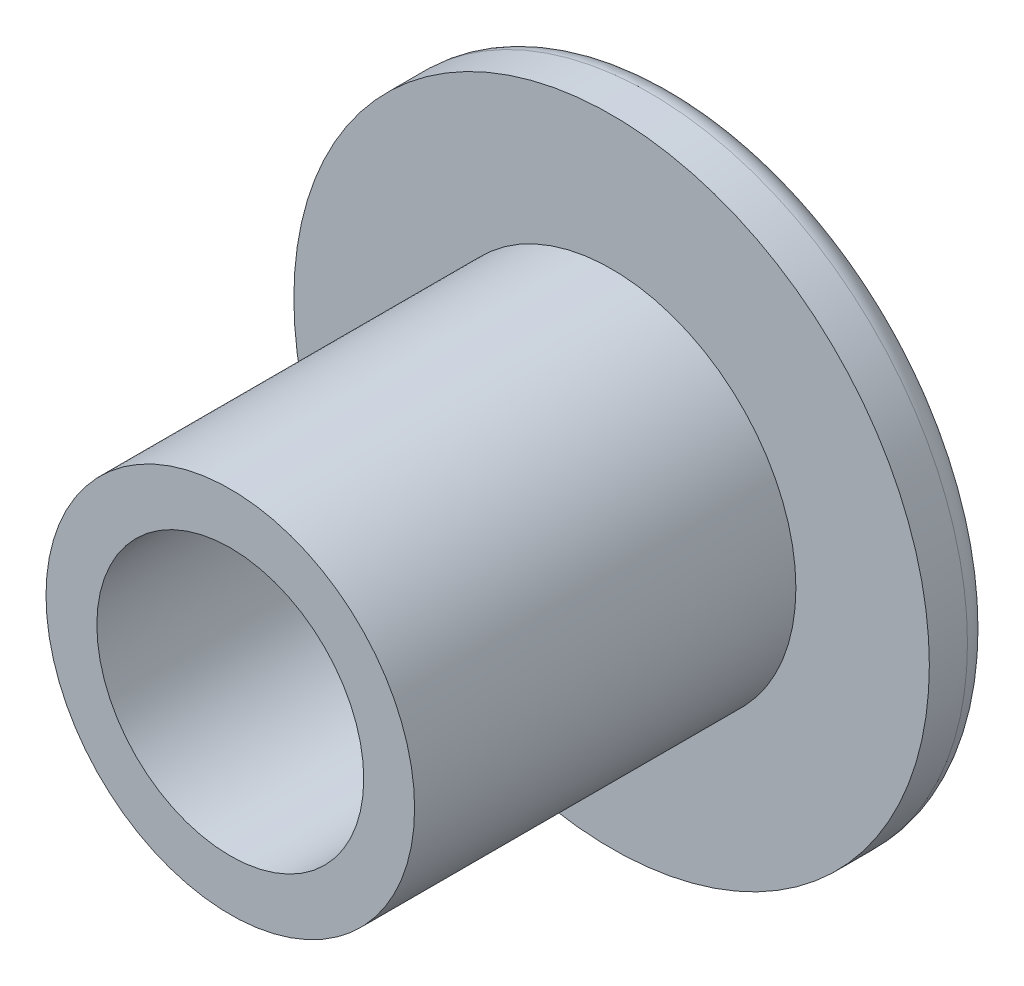
SolidWorks part; units mm, degrees
ref_plane "Front Plane" through (0, 0, 0) normal (0, 0, 1) x (1, 0, 0)
ref_plane "Top Plane" through (0, 0, 0) normal (0, 1, 0) x (1, 0, 0)
ref_plane "Right Plane" through (0, 0, 0) normal (1, 0, 0) x (0, 0, -1)
sketch "Sketch1" plane through (0, 0, 0) normal (0, 0, 1) x (1, 0, 0)
  circle A0 centre (0, 0) radius 5
  dimension "D1" = 10
extrude "Boss-Extrude1" add sketch "Sketch1" along normal blind 1 contours A0
sketch "Sketch2" plane through (0, 0, 1) normal (0, 0, 1) x (1, 0, 0)
  circle A0 centre (0, 0) radius 2.9
  dimension "D1" = 5.8
extrude "Boss-Extrude2" add sketch "Sketch2" along normal blind 6
sketch "Sketch3" plane through (0, 0, 7) normal (0, 0, 1) x (1, 0, 0)
  circle A0 centre (0, 0) radius 2.1
  dimension "D1" = 4.2
extrude "Cut-Extrude2" cut sketch "Sketch3" against normal through all both and the other way through all contours A0
fillet "Fillet1" radius 0.4 1 edges at (5, 0, 0)
fillet "Fillet2" radius 0.2 1 edges at (2.1, 0, 0)
